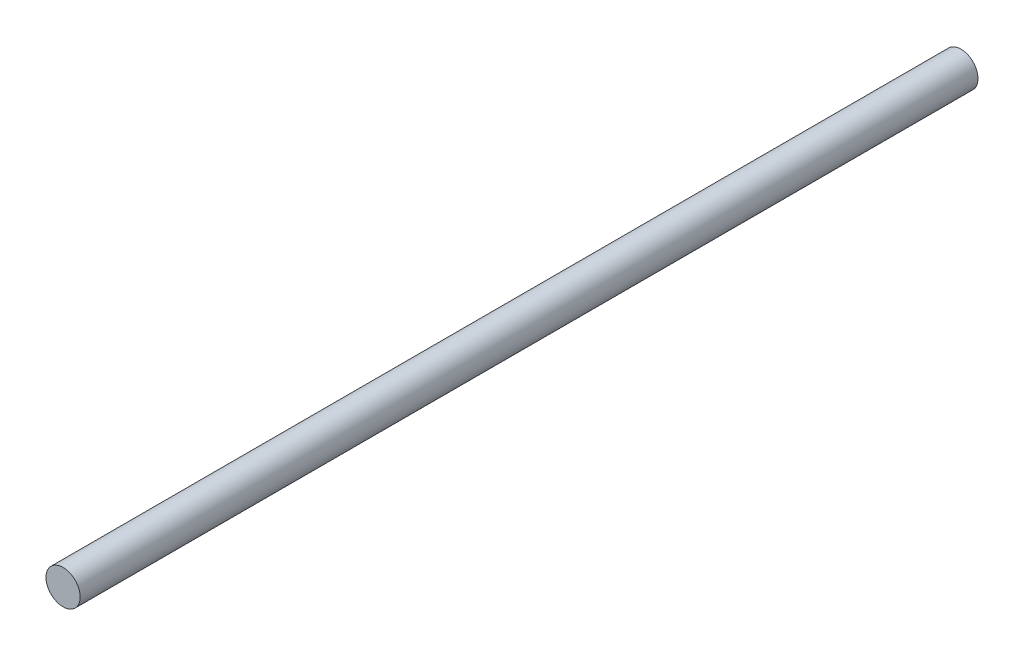
SolidWorks part; units mm, degrees
material "1060 Alloy"
ref_plane "Front Plane" through (0, 0, 0) normal (0, 0, 1) x (1, 0, 0)
ref_plane "Top Plane" through (0, 0, 0) normal (0, 1, 0) x (1, 0, 0)
ref_plane "Right Plane" through (0, 0, 0) normal (1, 0, 0) x (0, 0, -1)
sketch "Sketch1" plane through (0, 0, 0) normal (0, 0, 1) x (1, 0, 0)
  circle A0 centre (0, 0) radius 4
  dimension "D1" = 8
extrude "Boss-Extrude1" add sketch "Sketch1" along normal blind 210
